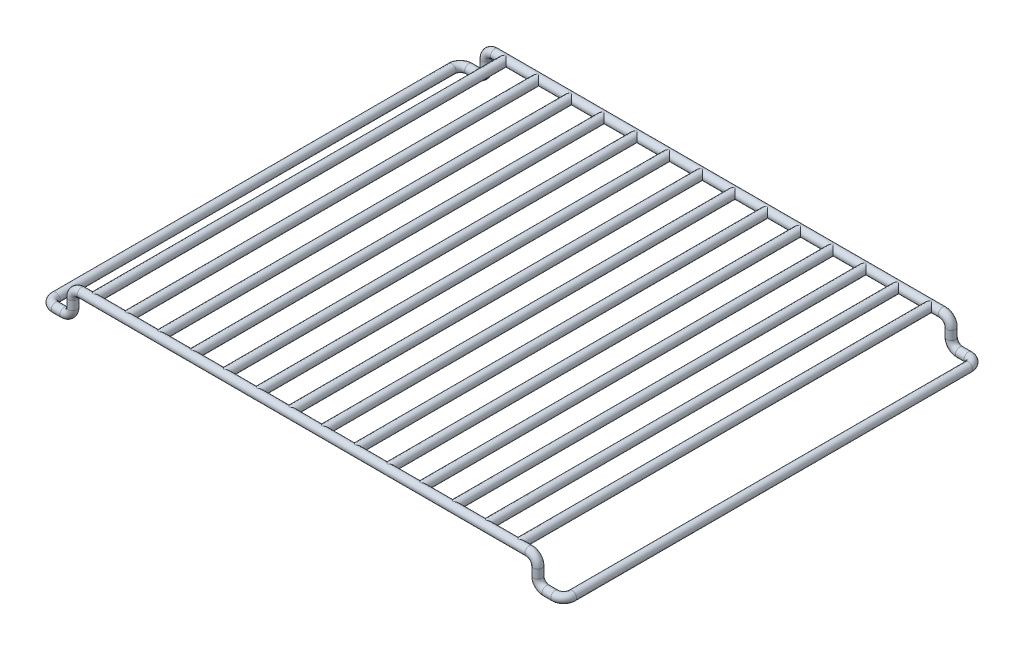
SolidWorks part; units mm, degrees
ref_plane "Front Plane" through (0, 0, 0) normal (0, 0, 1) x (1, 0, 0)
ref_plane "Top Plane" through (0, 0, 0) normal (0, 1, 0) x (1, 0, 0)
ref_plane "Right Plane" through (0, 0, 0) normal (1, 0, 0) x (0, 0, -1)
sketch3d "3DSketch1"
  line L0 (0, 0, -120) -> (0, 0, 120) construction
  line L1 (0, 0, 120) -> (130, 0, 120)
  line L2 (135, -5, 120) -> (135, -10, 120)
  line L3 (140, -15, 120) -> (145, -15, 120)
  line L4 (150, -15, 115) -> (150, -15, -115)
  line L5 (145, -15, -120) -> (140, -15, -120)
  line L6 (135, -10, -120) -> (135, -5, -120)
  line L7 (130, 0, -120) -> (0, 0, -120)
  arc A0 (135, -5, -120) -> (130, 0, -120) centre (130, -5, -120) ccw
  arc A1 (140, -15, -120) -> (135, -10, -120) centre (140, -10, -120) ccw
  arc A2 (150, -15, -115) -> (145, -15, -120) centre (145, -15, -115) ccw
  arc A3 (145, -15, 120) -> (150, -15, 115) centre (145, -15, 115) ccw
  arc A4 (135, -10, 120) -> (140, -15, 120) centre (140, -10, 120) ccw
  arc A5 (130, 0, 120) -> (135, -5, 120) centre (130, -5, 120) ccw
  point P4 (0, 0, 0)
  point P18 (135, 0, -120)
  point P19 (130, -5, -115)
  point P22 (135, -15, -120)
  point P23 (140, -10, -125)
  point P26 (150, -15, -120)
  point P27 (145, -10, -115)
  point P30 (150, -15, 120)
  point P31 (145, -10, 115)
  point P34 (135, -15, 120)
  point P35 (140, -10, 125)
  point P38 (135, 0, 120)
  point P39 (130, -5, 115)
  dimension "D5" = 5
  dimension "D1" = 240
  dimension "D2" = 135
  dimension "D3" = 15
  dimension "D4" = 15
sweep "Sweep1" add path "3DSketch1" circular profile diameter 5 parameters "D3"=5
sketch "Sketch14" plane through (0, 0, 0) normal (0, 0, 1) x (1, 0, 0)
  line L0 (0, 0) -> (130, 0) construction
  line L1 (0, 2.5) -> (0, -2.5) construction
  line L2 (130, 2.5) -> (0, 2.5) construction
  line L3 (9.5, 0) -> (28.5, 0) construction
  circle A0 centre (9.5, 0) radius 2.5
  circle A1 centre (28.5, 0) radius 2.5
  circle A2 centre (47.5, 0) radius 2.5
  circle A3 centre (66.5, 0) radius 2.5
  circle A4 centre (85.5, 0) radius 2.5
  circle A5 centre (104.5, 0) radius 2.5
  circle A6 centre (123.5, 0) radius 2.5
  dimension "D1" = 9.5
  dimension "D3" = 19
  dimension "D2" = 7
extrude "Boss-Extrude1" add sketch "Sketch14" along normal up to next and the other way up to next
mirror "Mirror1" about plane through (0, 0, 0) normal (1, 0, 0) of bodies 102
